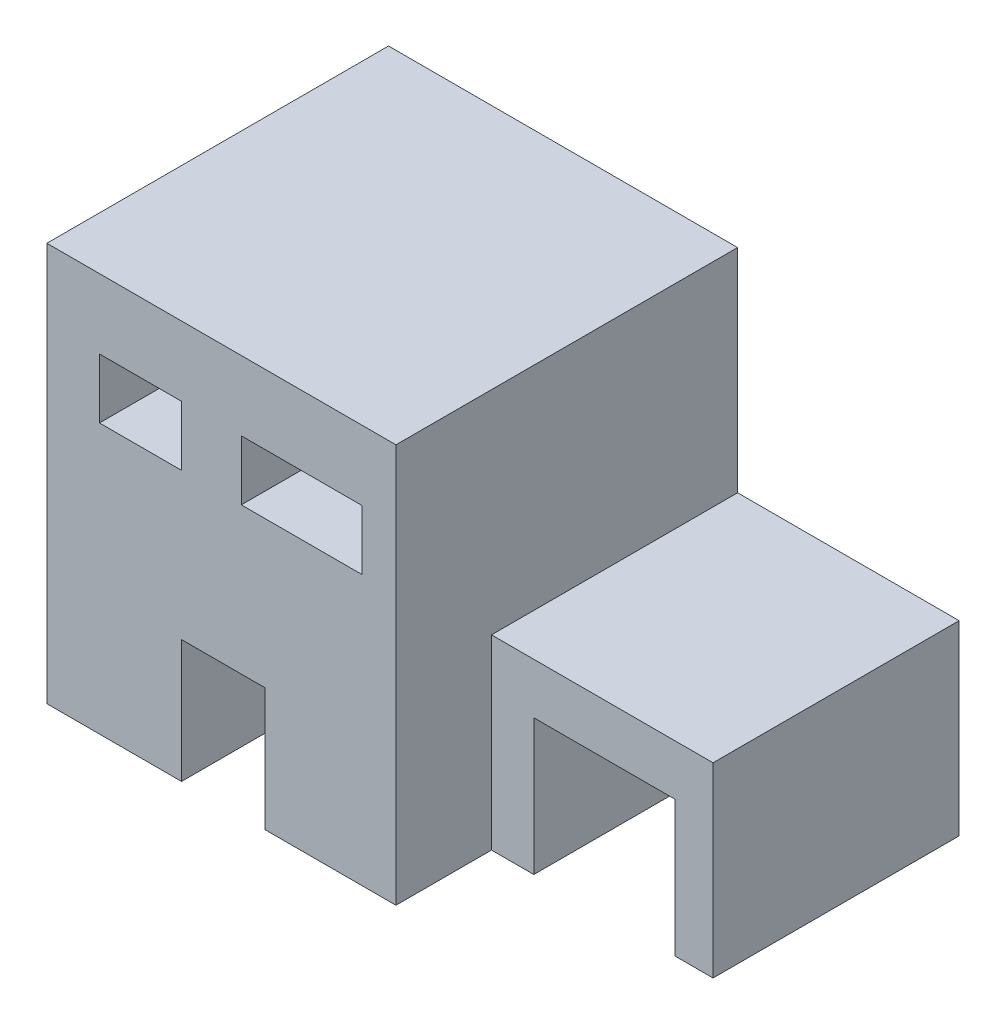
SolidWorks part; units mm, degrees
ref_plane "Plan de face" through (0, 0, 0) normal (0, 0, 1) x (1, 0, 0)
ref_plane "Plan de dessus" through (0, 0, 0) normal (0, 1, 0) x (1, 0, 0)
ref_plane "Plan de droite" through (0, 0, 0) normal (1, 0, 0) x (0, 0, -1)
sketch "Esquisse1" plane through (0, 0, 0) normal (0, 1, 0) x (1, 0, 0)
  line L1 (0, 0) -> (78.787, 0)
  line L2 (0, 0) -> (0, 77.1079)
  line L3 (0, 77.1079) -> (78.787, 77.1079)
  line L4 (78.787, 0) -> (78.787, 77.1079)
extrude "Boss.-Extru.1" add sketch "Esquisse1" along normal blind 90
sketch "Esquisse3" plane through (78.787, 0, 0) normal (1, 0, 0) x (0, 0, -1)
  line L0 (0, 0) -> (77.1079, 0) construction
  line L1 (21.5641, 0) -> (77.1079, 0)
  line L2 (21.5641, 0) -> (21.5641, 42.0686)
  line L3 (21.5641, 42.0686) -> (77.1079, 42.0686)
  line L4 (77.1079, 0) -> (77.1079, 42.0686)
  line L5 (77.1079, 90) -> (77.1079, 0) construction
extrude "Boss.-Extru.3" add sketch "Esquisse3" along normal blind 50
sketch "Esquisse4" plane through (0, 0, 0) normal (0, 0, 1) x (1, 0, 0)
  line L0 (0, 0) -> (78.787, 0) construction
  line L1 (30.3926, 0) -> (49.1791, 0)
  line L2 (30.3926, 0) -> (30.3926, 27.7349)
  line L3 (30.3926, 27.7349) -> (49.1791, 27.7349)
  line L4 (49.1791, 0) -> (49.1791, 27.7349)
  line L5 (128.787, 0) -> (78.787, 0) construction
  line L6 (88.3397, 0) -> (120.2238, 0)
  line L7 (88.3397, 0) -> (88.3397, 30.6455)
  line L8 (88.3397, 30.6455) -> (120.2238, 30.6455)
  line L9 (120.2238, 0) -> (120.2238, 30.6455)
  line L15 (11.8707, 74.3043) -> (30.3926, 74.3043)
  line L16 (11.8707, 74.3043) -> (11.8707, 60.8098)
  line L17 (11.8707, 60.8098) -> (30.3926, 60.8098)
  line L18 (30.3926, 74.3043) -> (30.3926, 60.8098)
  line L19 (43.8871, 74.3043) -> (71.1407, 74.3043)
  line L20 (43.8871, 74.3043) -> (43.8871, 60.8098)
  line L21 (43.8871, 60.8098) -> (71.1407, 60.8098)
  line L22 (71.1407, 74.3043) -> (71.1407, 60.8098)
extrude "Enlèv. mat.-Extru.1" cut sketch "Esquisse4" against normal blind 110
